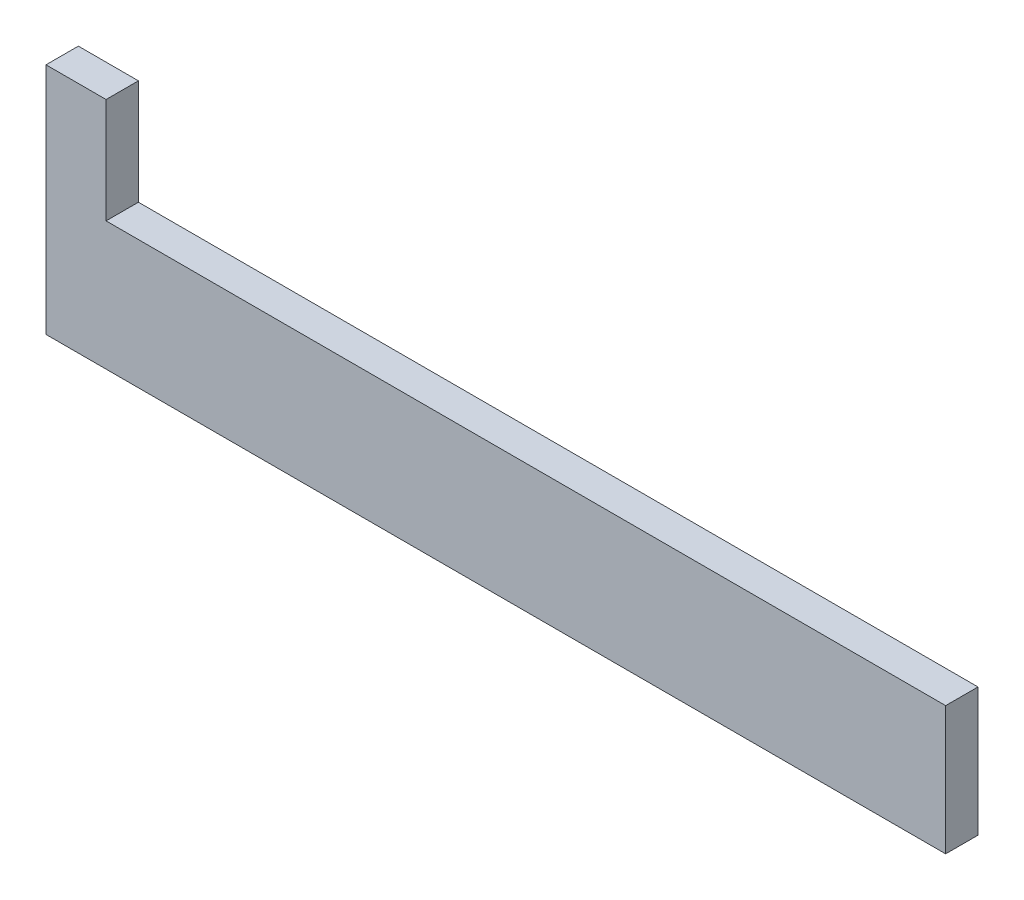
SolidWorks part; units mm, degrees
ref_plane "Front Plane" through (0, 0, 0) normal (0, 0, 1) x (1, 0, 0)
ref_plane "Top Plane" through (0, 0, 0) normal (0, 1, 0) x (1, 0, 0)
ref_plane "Right Plane" through (0, 0, 0) normal (1, 0, 0) x (0, 0, -1)
sketch "Sketch1" plane through (0, 0, 0) normal (0, 0, 1) x (1, 0, 0)
  line L0 (0, 0) -> (0, 13.0856) construction
  line L1 (28, 0) -> (-28, 0)
  line L2 (-28, 0) -> (-28, 15.549)
  line L3 (24, 8.549) -> (-24, 8.549)
  line L4 (-28, 15.549) -> (-24, 15.549)
  line L5 (-24, 15.549) -> (-24, 8.549)
  line L6 (24, 15.549) -> (24, 8.549)
  line L7 (28, 15.549) -> (24, 15.549)
  line L8 (28, 0) -> (28, 15.549)
  point P11 (0, 8.549)
  dimension "D1" = 28
  dimension "D2" = 8.549
  dimension "D3" = 4
  dimension "D4" = 7
extrude "Boss-Extrude1" add sketch "Sketch1" along normal blind 2.1537
sketch "Sketch3" plane through (24, 0, 0) normal (-1, 0, 0) x (0, 0, 1)
  line L1 (2.1537, 8.549) -> (0, 8.549)
  line L2 (2.1537, 8.549) -> (2.1537, 15.549)
  line L3 (2.1537, 15.549) -> (0, 15.549)
  line L4 (0, 8.549) -> (0, 15.549)
extrude "Cut-Extrude1" cut sketch "Sketch3" against normal up to next
sketch "Sketch4" plane through (28, 0, 0) normal (1, 0, 0) x (0, 0, -1)
  line L1 (0, 8.549) -> (-2.1537, 8.549)
  line L2 (0, 8.549) -> (0, 0)
  line L3 (0, 0) -> (-2.1537, 0)
  line L4 (-2.1537, 8.549) -> (-2.1537, 0)
extrude "Boss-Extrude2" add sketch "Sketch4" along normal blind 3.9
